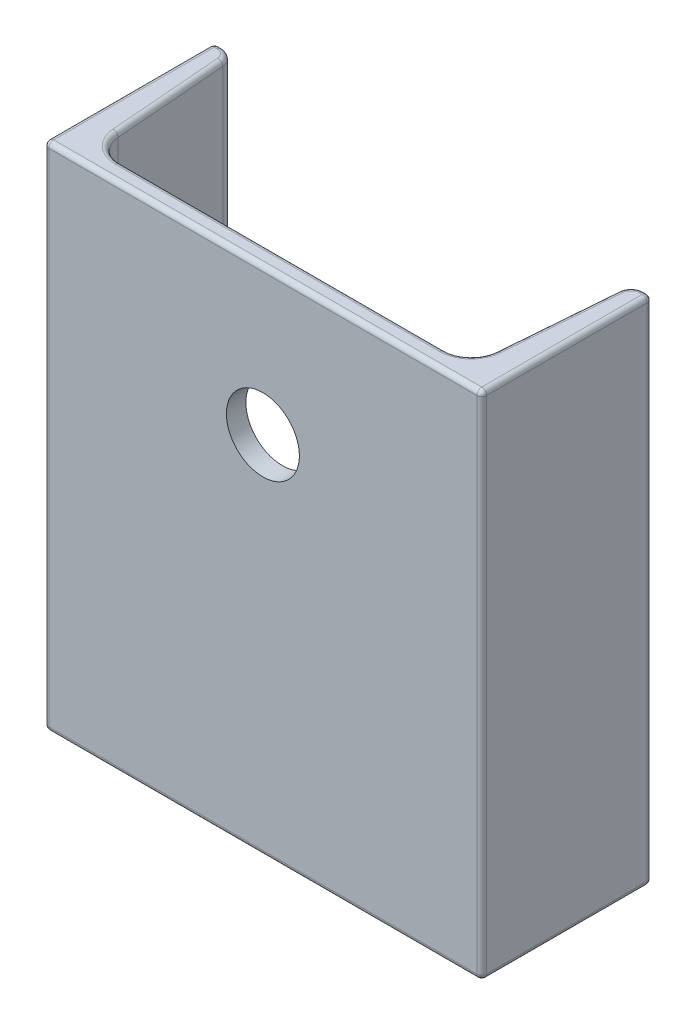
SolidWorks part; units mm, degrees
material "1.0037 (S235JR)"
ref_plane "Front Plane" through (0, 0, 0) normal (0, 0, 1) x (1, 0, 0)
ref_plane "Top Plane" through (0, 0, 0) normal (0, 1, 0) x (1, 0, 0)
ref_plane "Right Plane" through (0, 0, 0) normal (1, 0, 0) x (0, 0, -1)
sketch "Sketch1" plane through (0, 0, 0) normal (1, 0, 0) x (0, 0, -1)
  line L0 (0, 186.5789) -> (0, -23.4211)
  dimension "D1" = 210
other "Upn UPN180(1)"
ref_plane "Plane1" through (0, 186.5789, 0) normal (0, -1, 0) x (0, 0, -1)
sketch "Sketch110" plane through (0, 186.5789, 0) normal (0, -1, 0) x (0, 0, -1)
  line L0 (70, 180) -> (0, 180)
  line L1 (70, 0) -> (0, 0)
  line L2 (0, 180) -> (0, 0)
  line L3 (0, 90) -> (8, 90) construction
  line L5 (0, 11) -> (35, 11) construction
  line L6 (70, 180) -> (70, 176.8776)
  line L7 (70, 0) -> (70, 3.1224)
  line L12 (8, 156.6848) -> (8, 23.3152)
  line L17 (18.1228, 167.6498) -> (64.9386, 171.3951)
  line L18 (18.1228, 12.3502) -> (64.9386, 8.6049)
  arc A0 (64.9386, 171.3951) -> (70, 176.8776) centre (64.5, 176.8776) ccw
  arc A1 (64.9386, 8.6049) -> (70, 3.1224) centre (64.5, 3.1224) cw
  arc A9 (8, 23.3152) -> (18.1228, 12.3502) centre (19, 23.3152) ccw
  arc A10 (8, 156.6848) -> (18.1228, 167.6498) centre (19, 156.6848) cw
  point P10 (0, 90)
  point P11 (8, 90)
  point P12 (35, 180)
  point P13 (35, 0)
  point P16 (4, 90)
  point P17 (0, 0)
  dimension "D4" = 35
  dimension "RI" = 11
  dimension "D2" = 4.574
  dimension "RA" = 5.5
  dimension "Depth" = 180
  dimension "BF" = 70
  dimension "TW" = 8
  dimension "TF" = 11
sketch "Sketch17" plane through (0, 0, -8) normal (0, 0, -1) x (-1, 0, 0)
  line L0 (-23.3152, 186.5789) -> (-156.6848, 186.5789) construction
  line L1 (-23.3152, -23.4211) -> (-156.6848, -23.4211) construction
  circle A0 centre (-90, 126.5789) radius 15
  point P7 (-90, -23.4211)
  dimension "D1" = 30
  dimension "D2" = 60
extrude "Cut-Extrude1" cut sketch "Sketch17" against normal blind 10
fillet "Fillet1" radius 2 28 edges at (178.4388, 186.5789, -70) (90, 186.5789, 0) (1.5612, 186.5789, -70) (6.8532, 186.5789, -68.5412) (10.4775, 186.5789, -41.5307) (15.8536, 186.5789, -10.9176) (90, 186.5789, -8) (164.1464, 186.5789, -10.9176) (169.5225, 186.5789, -41.5307) (173.1468, 186.5789, -68.5412) (169.5225, -23.4211, -41.5307) (164.1464, -23.4211, -10.9176) (90, -23.4211, -8) (15.8536, -23.4211, -10.9176) (10.4775, -23.4211, -41.5307) (6.8532, -23.4211, -68.5412) (1.5612, -23.4211, -70) (90, -23.4211, 0) (178.4388, -23.4211, -70) (173.1468, -23.4211, -68.5412) (0, 81.5789, 0) (0, -23.4211, -35) (0, 81.5789, -70) (0, 186.5789, -35) (180, 81.5789, -70) (180, -23.4211, -35) (180, 81.5789, 0) (180, 186.5789, -35)
